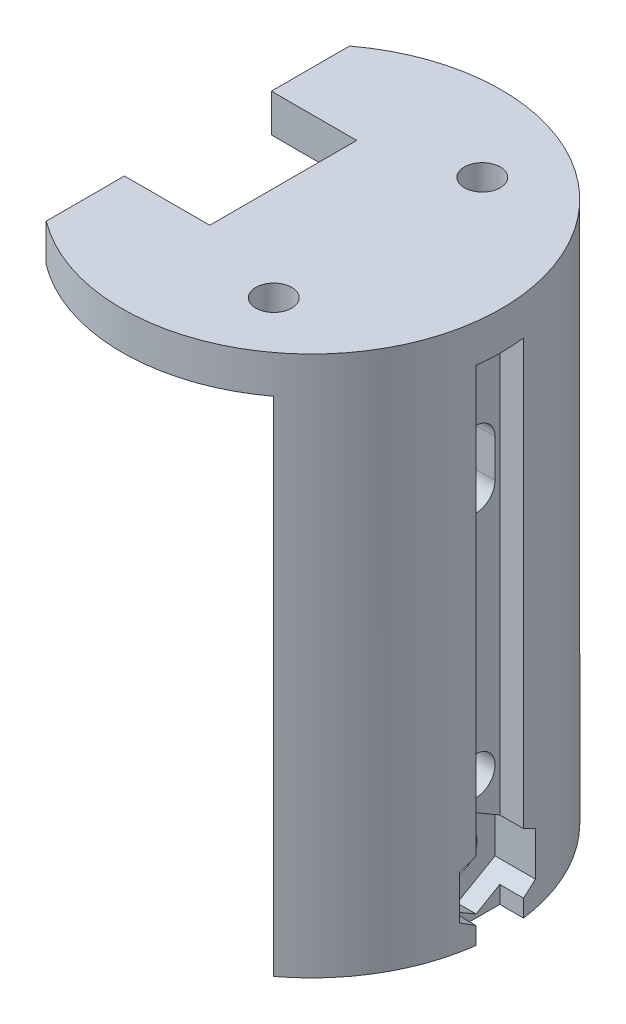
SolidWorks part; units mm, degrees
ref_plane "Front Plane" through (0, 0, 0) normal (0, 0, 1) x (1, 0, 0)
ref_plane "Top Plane" through (0, 0, 0) normal (0, 1, 0) x (1, 0, 0)
ref_plane "Right Plane" through (0, 0, 0) normal (1, 0, 0) x (0, 0, -1)
sketch "Sketch2" plane through (0, 0, 0) normal (0, 1, 0) x (1, 0, 0)
  line L0 (-3.81, 25.1126) -> (-3.81, -25.1126) construction
  line L1 (-15.24, -20.32) -> (-15.24, -9.8425)
  line L2 (-20.6326, -9.8425) -> (16.7847, -9.8425) construction
  line L3 (-15.24, -9.8425) -> (-3.81, -9.8425)
  line L4 (-3.81, -9.8425) -> (-3.81, 9.8425)
  line L5 (16.7847, 9.8425) -> (-20.6326, 9.8425) construction
  line L6 (-3.81, 9.8425) -> (-15.24, 9.8425)
  line L7 (-15.24, 9.8425) -> (-15.24, 20.32)
  line L8 (-15.24, -20.32) -> (-15.24, 20.32) construction
  circle A2 centre (0, 0) radius 25.4 construction
  arc A3 (-15.24, -20.32) -> (-15.24, 20.32) centre (0, 0) ccw
  dimension "D1" = 3.81
  dimension "D2" = 15.24
extrude "plate" add sketch "Sketch2" along normal blind 5.08
sketch "Sketch15" plane through (0, 0, 0) normal (0, -1, 0) x (1, 0, 0)
  circle A1 centre (8.89, 13.97) radius 2.413
  circle A2 centre (8.89, 13.97) radius 2.413 construction
  circle A3 centre (8.89, -13.97) radius 2.413
  circle A4 centre (8.89, -13.97) radius 2.413 construction
extrude "boltholes" cut sketch "Sketch15" against normal up to next
sketch "Sketch16" plane through (0, 0, 0) normal (0, -1, 0) x (1, 0, 0)
  line L5 (25.2008, 3.175) -> (25.2008, -3.175) construction
  line L6 (15.24, 20.32) -> (15.24, -20.32)
  line L12 (0, 0) -> (25.2008, 0) construction
  line L13 (25.2008, 3.175) -> (22.0258, 3.175)
  line L14 (22.0258, 3.175) -> (22.0258, -3.175)
  line L15 (22.0258, -3.175) -> (25.2008, -3.175)
  arc A0 (-15.24, -20.32) -> (-15.24, 20.32) centre (0, 0) ccw construction
  arc A2 (15.24, 20.32) -> (25.2008, 3.175) centre (0, 0) cw
  arc A3 (15.24, -20.32) -> (25.2008, -3.175) centre (0, 0) ccw
  dimension "D1" = 6.35
  dimension "D4" = 15.24
  dimension "D2" = 3.175
extrude "upright" add sketch "Sketch16" along normal blind 67.31
sketch "Sketch17" plane through (15.24, 0, 0) normal (-1, 0, 0) x (0, 0, 1)
  line L0 (0, 0) -> (0, -67.31) construction
  line L1 (-9.8425, 0) -> (9.8425, 0) construction
  line L2 (-3.175, -67.31) -> (3.175, -67.31) construction
  line L3 (0, -12.7) -> (0, -17.78) construction
  line L4 (2.54, -12.7) -> (2.54, -17.78)
  line L5 (-2.54, -12.7) -> (-2.54, -17.78)
  arc A1 (2.54, -12.7) -> (-2.54, -12.7) centre (0, -12.7) ccw
  arc A2 (-2.54, -17.78) -> (2.54, -17.78) centre (0, -17.78) ccw
  circle A3 centre (0, -50.8) radius 2.54
  circle A4 centre (0, -60.96) radius 2.667
  point P8 (0, -15.24)
  point P17 (0, -58.42)
  dimension "D1" = 5.08
  dimension "D3" = 12.7
  dimension "D4" = 5.08
  dimension "D6" = 10.16
  dimension "D7" = 5.334
  dimension "D2" = 5.08
  dimension "D5" = 38.1
extrude "upright_boltholes" cut sketch "Sketch17" against normal up to next
sketch "Sketch18" plane through (22.0258, 0, 0) normal (1, 0, 0) x (0, 0, -1)
  line L1 (0, -66.8259) -> (5.08, -63.8929)
  line L2 (5.08, -63.8929) -> (5.08, -58.0271)
  line L3 (5.08, -58.0271) -> (0, -55.0941)
  line L4 (0, -55.0941) -> (-5.08, -58.0271)
  line L5 (-5.08, -58.0271) -> (-5.08, -63.8929)
  line L6 (-5.08, -63.8929) -> (0, -66.8259)
  circle A0 centre (0, -60.96) radius 5.08 construction
  dimension "D1" = 10.16
extrude "nut_hole" cut sketch "Sketch18" against normal blind 2.54 and the other way up to next
